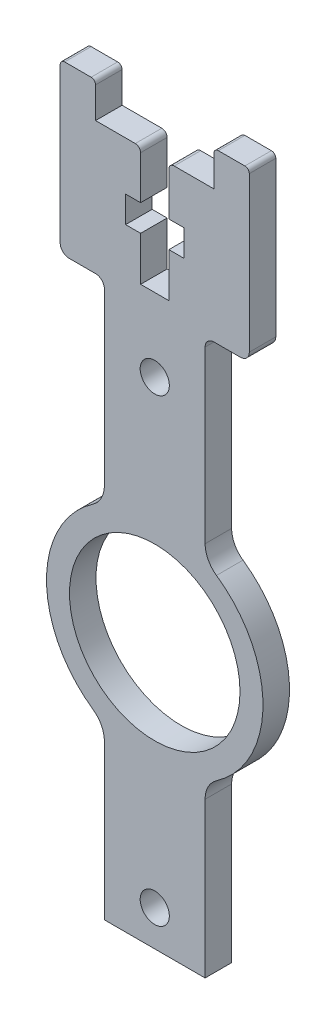
SolidWorks part; units mm, degrees
material "6061 合金"
ref_plane "前视基准面" through (0, 0, 0) normal (0, 0, 1) x (1, 0, 0)
ref_plane "上视基准面" through (0, 0, 0) normal (0, 1, 0) x (1, 0, 0)
ref_plane "右视基准面" through (0, 0, 0) normal (1, 0, 0) x (0, 0, -1)
sketch "草图1" plane through (0, 0, 0) normal (0, 0, 1) x (1, 0, 0)
  line L0 (0, 0) -> (4, 0)
  line L1 (4, 0) -> (4, -4)
  line L2 (4, -4) -> (9.1, -4)
  line L3 (9.1, -4) -> (9.1, -9.5)
  line L4 (9.1, -9.5) -> (7.4, -9.5)
  line L5 (7.4, -9.5) -> (7.4, -12.5)
  line L6 (7.4, -12.5) -> (9.1, -12.5)
  line L7 (9.1, -12.5) -> (9.1, -17.5)
  line L8 (9.1, -17.5) -> (12.3, -17.5)
  line L9 (12.3, -17.5) -> (12.3, -12.5)
  line L10 (12.3, -12.5) -> (14, -12.5)
  line L11 (14, -12.5) -> (14, -9.5)
  line L12 (14, -9.5) -> (12.3, -9.5)
  line L13 (12.3, -9.5) -> (12.3, -4)
  line L14 (12.3, -4) -> (17.4, -4)
  line L15 (17.4, -4) -> (17.4, 0)
  line L16 (17.4, 0) -> (21.4, 0)
  line L17 (21.4, 0) -> (21.4, -4)
  line L18 (0, 0) -> (0, -4)
  line L19 (0, -4) -> (0, -19)
  line L20 (0, -19) -> (5, -19)
  line L21 (5, -19) -> (5, -40.9569)
  line L22 (21.4, -4) -> (21.4, -19)
  line L23 (21.4, -19) -> (16.4, -19)
  line L24 (16.4, -19) -> (16.4, -40.9569)
  line L25 (10.7, -17.5) -> (10.7, -51.8) construction
  line L26 (10.7, -51.8) -> (10.7, -77.8) construction
  line L34 (5, -81.8431) -> (16.4, -81.8431)
  line L35 (16.4, -81.8431) -> (16.4, -62.6431)
  line L36 (5, -62.6431) -> (5, -81.8431)
  circle A0 centre (10.7, -51.8) radius 9.65
  circle A2 centre (10.7, -25.8) radius 1.65
  circle A3 centre (10.7, -77.8) radius 1.65
  arc A4 (16.4, -62.6431) -> (16.4, -40.9569) centre (10.7, -51.8) ccw
  arc A5 (5, -40.9569) -> (5, -62.6431) centre (10.7, -51.8) ccw
  dimension "D19" = 34.3
  dimension "D20" = 19.3
  dimension "D21" = 24.5
  dimension "D24" = 26
  dimension "D25" = 3.3
  dimension "D26" = 3.3
  dimension "D1" = 3.2
  dimension "D2" = 5
  dimension "D3" = 5
  dimension "D4" = 3
  dimension "D5" = 3
  dimension "D6" = 1.7
  dimension "D7" = 1.7
  dimension "D8" = 1.7
  dimension "D9" = 1.7
  dimension "D10" = 5.5
  dimension "D11" = 5.5
  dimension "D12" = 4
  dimension "D13" = 4
  dimension "D14" = 4
  dimension "D15" = 4
  dimension "D16" = 4
  dimension "D17" = 5.1
  dimension "D18" = 5.1
  dimension "D22" = 5
  dimension "D23" = 5
  dimension "D27" = 26
  dimension "D28" = 19.2
  dimension "D29" = 15
  dimension "D30" = 15
  dimension "D31" = 11.4
  dimension "D32" = 19.2
extrude "凸台-拉伸1" add sketch "草图1" along normal blind 3
fillet "圆角2" radius 1 4 edges at (21.4, -19, 1.5) (5, -19, 1.5) (0, -19, 1.5) (16.4, -19, 1.5)
fillet "圆角3" radius 0.6 2 edges at (12.3, -4, 1.5) (9.1, -4, 1.5)
fillet "圆角4" radius 0.5 4 edges at (21.4, 0, 1.5) (17.4, 0, 1.5) (0, 0, 1.5) (4, 0, 1.5)
fillet "圆角5" radius 3 4 edges at (5, -62.6431, 1.5) (16.4, -62.6431, 1.5) (16.4, -40.9569, 1.5) (5, -40.9569, 1.5)
